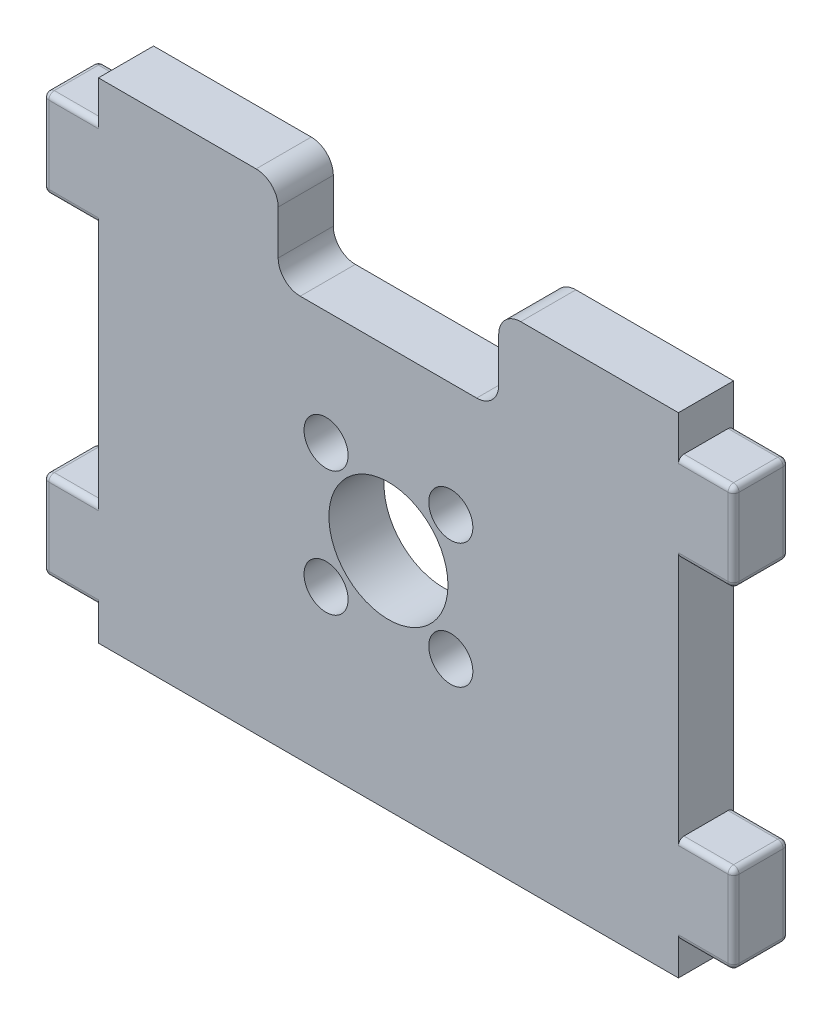
SolidWorks part; units mm, degrees
ref_plane "Alzado" through (0, 0, 0) normal (0, 0, 1) x (1, 0, 0)
ref_plane "Planta" through (0, 0, 0) normal (0, 1, 0) x (1, 0, 0)
ref_plane "Vista lateral" through (0, 0, 0) normal (1, 0, 0) x (0, 0, -1)
sketch "Croquis1" plane through (0, 0, 0) normal (0, 0, 1) x (1, 0, 0)
  line L0 (-5.6569, 4.1569) -> (5.6569, -7.1569) construction
  line L1 (26.3, -22.5) -> (-26.3, -22.5)
  line L2 (26.3, -22.5) -> (26.3, 22.5)
  line L3 (26.3, 22.5) -> (-26.3, 22.5)
  line L4 (-26.3, -22.5) -> (-26.3, 22.5)
  line L5 (26.3, -22.5) -> (-26.3, 22.5) construction
  line L6 (26.3, 22.5) -> (-26.3, -22.5) construction
  line L7 (-5.6569, -7.1569) -> (5.6569, 4.1569) construction
  circle A0 centre (0, -1.5) radius 5.4
  circle A1 centre (0, -1.5) radius 5.1 construction
  circle A2 centre (0, -1.5) radius 8 construction
  circle A3 centre (-5.6569, 4.1569) radius 2
  circle A4 centre (5.6569, 4.1569) radius 2
  circle A5 centre (5.6569, -7.1569) radius 2
  circle A6 centre (-5.6569, -7.1569) radius 2
  point P0 (0, 0)
  point P8 (0, -1.5)
  point P19 (0, 0)
  point P20 (-6.3115, 37.5344)
  point P21 (0, 0)
  point P22 (8.4849, -22.1528)
  point P23 (0, 0)
  point P25 (0, 3.2602)
  point P26 (0, 0)
  dimension "D3" = 10.8
  dimension "D4" = 10.2
  dimension "D5" = 16
  dimension "D6" = 4
  dimension "D1" = 52.6
  dimension "D2" = 45
  dimension "D7" = 90
  dimension "D8" = 1.5
extrude "Saliente-Extruir1" add sketch "Croquis1" along normal blind 5
sketch "Croquis2" plane through (-26.3, 0, 0) normal (-1, 0, 0) x (0, 0, 1)
  line L0 (0, 22.5) -> (0, -22.5) construction
  line L1 (0, 19) -> (5, 19)
  line L2 (0, 19) -> (0, 11)
  line L3 (0, 11) -> (5, 11)
  line L4 (5, 19) -> (5, 11)
  line L5 (5, 22.5) -> (5, -22.5) construction
  line L6 (0, 0) -> (-5.5675, 0) construction
  line L7 (5, -19) -> (5, -11)
  line L8 (0, -11) -> (5, -11)
  line L9 (0, -19) -> (0, -11)
  line L10 (0, -19) -> (5, -19)
  point P8 (5, 15)
  dimension "D1" = 8
  dimension "D2" = 15
extrude "Saliente-Extruir2" add sketch "Croquis2" along normal blind 5
fillet "Redondeo1" radius 0.5 16 edges at (-31.3, -15, 0) (-31.3, -11, 2.5) (-31.3, -15, 5) (-31.3, -19, 2.5) (-31.3, 19, 2.5) (-31.3, 15, 5) (-31.3, 11, 2.5) (-31.3, 15, 0) (-28.8, -19, 5) (-28.8, -11, 5) (-28.8, -19, 0) (-28.8, -11, 0) (-28.8, 11, 0) (-28.8, 11, 5) (-28.8, 19, 0) (-28.8, 19, 5)
mirror "Simetría1" about plane through (0, 0, 0) normal (1, 0, 0) of "Saliente-Extruir2", "Redondeo1"
sketch "Croquis3" plane through (0, 0, 5) normal (0, 0, 1) x (1, 0, 0)
  line L0 (26.3, 22.5) -> (-26.3, 22.5) construction
  line L1 (-10, 22.5) -> (10, 22.5)
  line L2 (-10, 22.5) -> (-10, 14.5)
  line L3 (-10, 14.5) -> (10, 14.5)
  line L4 (10, 22.5) -> (10, 14.5)
  point P6 (0, 14.5)
  dimension "D1" = 8
  dimension "D2" = 20
extrude "Cortar-Extruir1" cut sketch "Croquis3" against normal blind 5
fillet "Redondeo2" radius 2 4 edges at (10, 22.5, 2.5) (10, 14.5, 2.5) (-10, 14.5, 2.5) (-10, 22.5, 2.5)
sketch "Croquis4" plane through (0, 0, 5) normal (0, 0, 1) x (1, 0, 0)
  line L0 (26.3, -22.5) -> (26.3, -18.5) construction
  line L1 (-26.3, -22.5) -> (26.3, -22.5)
  line L2 (-26.3, -22.5) -> (-26.3, -21.9)
  line L3 (-26.3, -21.9) -> (26.3, -21.9)
  line L4 (26.3, -22.5) -> (26.3, -21.9)
  dimension "D1" = 0.6
extrude "Cortar-Extruir2" cut sketch "Croquis4" against normal blind 5
